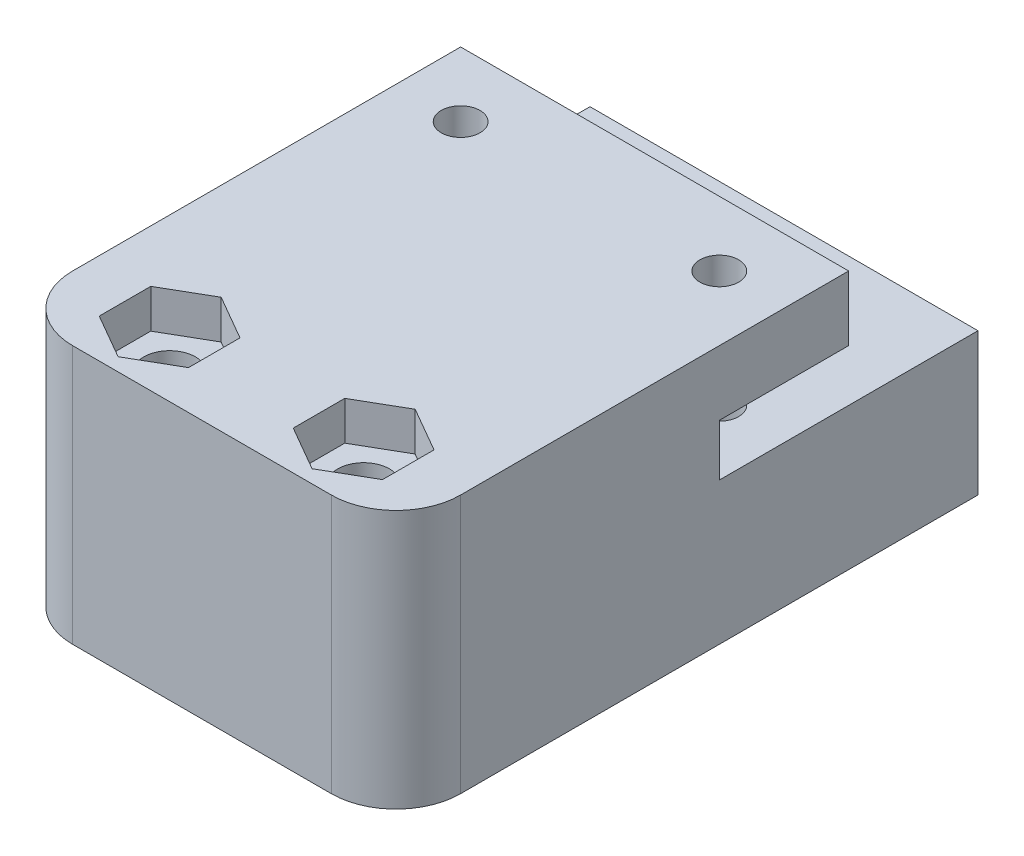
SolidWorks part; units mm, degrees
ref_plane "Alzado" through (0, 0, 0) normal (0, 0, 1) x (1, 0, 0)
ref_plane "Planta" through (0, 0, 0) normal (0, 1, 0) x (1, 0, 0)
ref_plane "Vista lateral" through (0, 0, 0) normal (1, 0, 0) x (0, 0, -1)
sketch "Croquis1" plane through (0, 0, 0) normal (0, 1, 0) x (1, 0, 0)
  line L0 (0, 30) -> (5, 30) construction
  line L1 (0, 0) -> (30, 0)
  line L2 (0, 0) -> (0, 35)
  line L3 (0, 35) -> (30, 35)
  line L4 (30, 0) -> (30, 35)
  line L5 (5, 30) -> (25, 30) construction
  line L6 (25, 30) -> (30, 30) construction
  line L7 (15, 30) -> (15, 35) construction
  line L8 (0, 5) -> (7.5, 5) construction
  line L9 (7.5, 5) -> (22.5, 5) construction
  line L10 (22.5, 5) -> (30, 5) construction
  line L11 (15, 30) -> (15, 5) construction
  circle A0 centre (25, 30) radius 1.5
  circle A1 centre (5, 30) radius 1.5
  circle A2 centre (7.5, 5) radius 2
  circle A3 centre (22.5, 5) radius 2
  dimension "D3" = 3
  dimension "D6" = 4
  dimension "D1" = 30
  dimension "D2" = 35
  dimension "D4" = 20
  dimension "D5" = 5
  dimension "D7" = 15
  dimension "D8" = 5
extrude "Saliente-Extruir1" add sketch "Croquis1" along normal blind 20
sketch "Croquis2" plane through (30, 0, 0) normal (1, 0, 0) x (0, 0, -1)
  line L0 (35, 20) -> (35, 0) construction
  line L1 (35, 11) -> (25, 11)
  line L2 (35, 11) -> (35, 15)
  line L3 (35, 15) -> (25, 15)
  line L4 (25, 11) -> (25, 15)
  line L5 (0, 20) -> (35, 20) construction
  dimension "D1" = 10
  dimension "D2" = 4
  dimension "D3" = 5
extrude "Cortar-Extruir1" cut sketch "Croquis2" against normal blind 41
sketch "Croquis3" plane through (0, 0, 0) normal (0, -1, 0) x (1, 0, 0)
  line L1 (5, -33.1177) -> (7.7, -31.5588)
  line L2 (7.7, -31.5588) -> (7.7, -28.4412)
  line L3 (7.7, -28.4412) -> (5, -26.8823)
  line L4 (5, -26.8823) -> (2.3, -28.4412)
  line L5 (2.3, -28.4412) -> (2.3, -31.5588)
  line L6 (2.3, -31.5588) -> (5, -33.1177)
  line L7 (25, -33.1177) -> (27.7, -31.5588)
  line L8 (27.7, -31.5588) -> (27.7, -28.4412)
  line L9 (27.7, -28.4412) -> (25, -26.8823)
  line L10 (25, -26.8823) -> (22.3, -28.4412)
  line L11 (22.3, -28.4412) -> (22.3, -31.5588)
  line L12 (22.3, -31.5588) -> (25, -33.1177)
  circle A0 centre (5, -30) radius 2.7 construction
  circle A1 centre (25, -30) radius 2.7 construction
  dimension "D1" = 5.4
extrude "Cortar-Extruir2" cut sketch "Croquis3" against normal blind 2
sketch "Croquis4" plane through (0, 0, 0) normal (0, -1, 0) x (1, 0, 0)
  line L1 (7.5, -8.9837) -> (10.95, -6.9919)
  line L2 (10.95, -6.9919) -> (10.95, -3.0081)
  line L3 (10.95, -3.0081) -> (7.5, -1.0163)
  line L4 (7.5, -1.0163) -> (4.05, -3.0081)
  line L5 (4.05, -3.0081) -> (4.05, -6.9919)
  line L6 (4.05, -6.9919) -> (7.5, -8.9837)
  line L7 (22.5, -8.9837) -> (25.95, -6.9919)
  line L8 (25.95, -6.9919) -> (25.95, -3.0081)
  line L9 (25.95, -3.0081) -> (22.5, -1.0163)
  line L10 (22.5, -1.0163) -> (19.05, -3.0081)
  line L11 (19.05, -3.0081) -> (19.05, -6.9919)
  line L12 (19.05, -6.9919) -> (22.5, -8.9837)
  circle A0 centre (7.5, -5) radius 3.45 construction
  circle A1 centre (22.5, -5) radius 3.45 construction
  dimension "D1" = 6.9
extrude "Cortar-Extruir3" cut sketch "Croquis4" against normal blind 3
sketch "Croquis5" plane through (0, 20, 0) normal (0, 1, 0) x (1, 0, 0)
  line L0 (22.5, 1.0163) -> (19.05, 3.0081) construction
  line L1 (25.95, 3.0081) -> (22.5, 1.0163) construction
  line L2 (25.95, 6.9919) -> (25.95, 3.0081) construction
  line L3 (22.5, 8.9837) -> (25.95, 6.9919) construction
  line L4 (19.05, 6.9919) -> (22.5, 8.9837) construction
  line L5 (19.05, 3.0081) -> (19.05, 6.9919) construction
  line L6 (4.05, 6.9919) -> (7.5, 8.9837) construction
  line L7 (7.5, 8.9837) -> (10.95, 6.9919) construction
  line L8 (10.95, 6.9919) -> (10.95, 3.0081) construction
  line L9 (10.95, 3.0081) -> (7.5, 1.0163) construction
  line L10 (7.5, 1.0163) -> (4.05, 3.0081) construction
  line L11 (4.05, 3.0081) -> (4.05, 6.9919) construction
  line L12 (22.5, 1.0163) -> (19.05, 3.0081)
  line L13 (25.95, 3.0081) -> (22.5, 1.0163)
  line L14 (25.95, 6.9919) -> (25.95, 3.0081)
  line L15 (22.5, 8.9837) -> (25.95, 6.9919)
  line L16 (19.05, 6.9919) -> (22.5, 8.9837)
  line L17 (19.05, 3.0081) -> (19.05, 6.9919)
  line L18 (4.05, 6.9919) -> (7.5, 8.9837)
  line L19 (7.5, 8.9837) -> (10.95, 6.9919)
  line L20 (10.95, 6.9919) -> (10.95, 3.0081)
  line L21 (10.95, 3.0081) -> (7.5, 1.0163)
  line L22 (7.5, 1.0163) -> (4.05, 3.0081)
  line L23 (4.05, 3.0081) -> (4.05, 6.9919)
extrude "Cortar-Extruir4" cut sketch "Croquis5" against normal blind 3
fillet "Redondeo1" radius 5 2 edges at (30, 10, 0) (0, 10, 0)
sketch "Croquis6" plane through (0, 0, -35) normal (0, 0, -1) x (-1, 0, 0)
  line L4 (0, 0) -> (0, 11)
  line L5 (0, 11) -> (-30, 11)
  line L6 (-30, 11) -> (-30, 0)
  line L7 (-30, 0) -> (0, 0)
  line L8 (0, 0) -> (0, 11)
  line L9 (0, 11) -> (-30, 11)
  line L10 (-30, 11) -> (-30, 0)
  line L11 (-30, 0) -> (0, 0)
  dimension "D1" = 0
extrude "Saliente-Extruir2" add sketch "Croquis6" along normal blind 10
